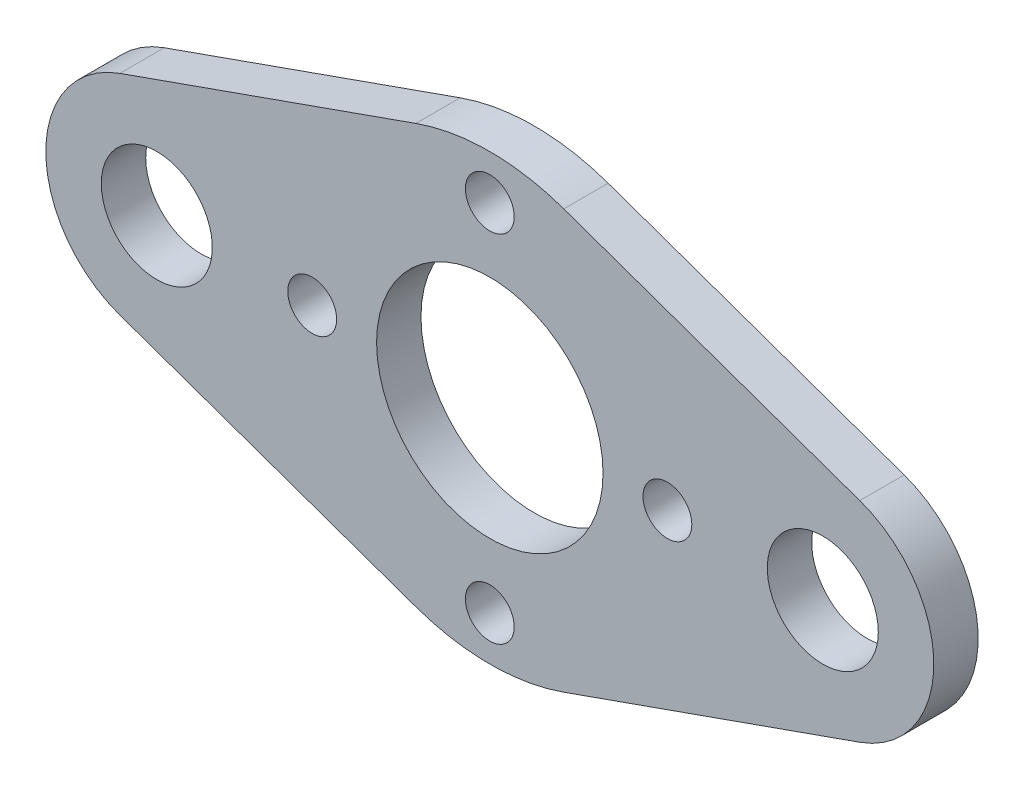
SolidWorks part; units mm, degrees
material "Thornel Mat VMA"
ref_plane "前视基准面" through (0, 0, 0) normal (0, 0, 1) x (1, 0, 0)
ref_plane "上视基准面" through (0, 0, 0) normal (0, 1, 0) x (1, 0, 0)
ref_plane "右视基准面" through (0, 0, 0) normal (1, 0, 0) x (0, 0, -1)
sketch "草图1" plane through (0, 0, 0) normal (0, 0, 1) x (1, 0, 0)
  line L5 (0, 0) -> (15, 0) construction
  line L6 (3.3333, 9.4281) -> (16.6667, 4.714)
  line L7 (3.3333, -9.4281) -> (16.6667, -4.714)
  line L10 (0, 0) -> (0, 50000) construction
  line L11 (-3.3333, -9.4281) -> (-16.6667, -4.714)
  line L12 (-3.3333, 9.4281) -> (-16.6667, 4.714)
  circle A2 centre (0, 8) radius 1.1
  circle A3 centre (8, 0) radius 1.1
  circle A4 centre (0, -8) radius 1.1
  circle A5 centre (-8, 0) radius 1.1
  circle A6 centre (0, 0) radius 5.1
  arc A7 (16.6667, -4.714) -> (16.6667, 4.714) centre (15, 0) ccw
  arc A8 (3.3333, 9.4281) -> (-3.3333, 9.4281) centre (0, 0) ccw
  circle A9 centre (15, 0) radius 2.5
  arc A10 (-3.3333, -9.4281) -> (-3.3333, 9.4281) centre (0, 0) ccw construction
  circle A11 centre (15, 0) radius 5 construction
  circle A14 centre (-15, 0) radius 2.5
  arc A15 (-16.6667, -4.714) -> (-16.6667, 4.714) centre (-15, 0) cw
  arc A20 (-3.3333, -9.4281) -> (3.3333, -9.4281) centre (0, 0) ccw
  point P18 (0, 0)
  dimension "D1" = 10
  dimension "D2" = 20
  dimension "D3" = 2.2
  dimension "D4" = 8
  dimension "D6" = 10.2
  dimension "D7" = 5
  dimension "D9" = 20
  dimension "D10" = 10
  dimension "D8" = 15
  dimension "D5" = 4
extrude "凸台-拉伸1" add sketch "草图1" along normal blind 2
